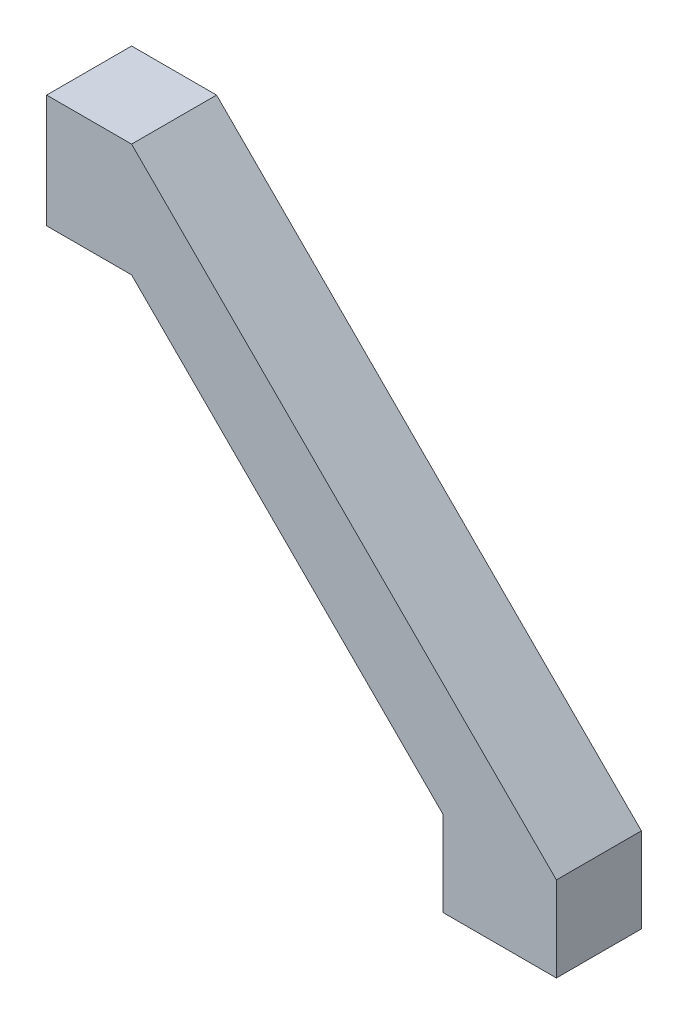
SolidWorks part; units mm, degrees
ref_plane "Plan de face" through (0, 0, 0) normal (0, 0, 1) x (1, 0, 0)
ref_plane "Plan de dessus" through (0, 0, 0) normal (0, 1, 0) x (1, 0, 0)
ref_plane "Plan de droite" through (0, 0, 0) normal (1, 0, 0) x (0, 0, -1)
sketch "Esquisse2" plane through (0, 0, 0) normal (0, 0, 1) x (1, 0, 0)
  line L0 (0, 0) -> (0, 6)
  line L1 (0, 6) -> (-30, 36)
  line L2 (-30, 36) -> (-36, 36)
  line L3 (-36, 36) -> (-36, 28)
  line L4 (-36, 28) -> (-30, 28)
  line L5 (-30, 28) -> (-8, 6)
  line L6 (-8, 6) -> (-8, 0)
  line L7 (-8, 0) -> (0, 0)
  dimension "D1" = 6
  dimension "D2" = 8
  dimension "D3" = 6
  dimension "D4" = 8
  dimension "D5" = 30
extrude "Boss.-Extru.1" add sketch "Esquisse2" along normal blind 6
